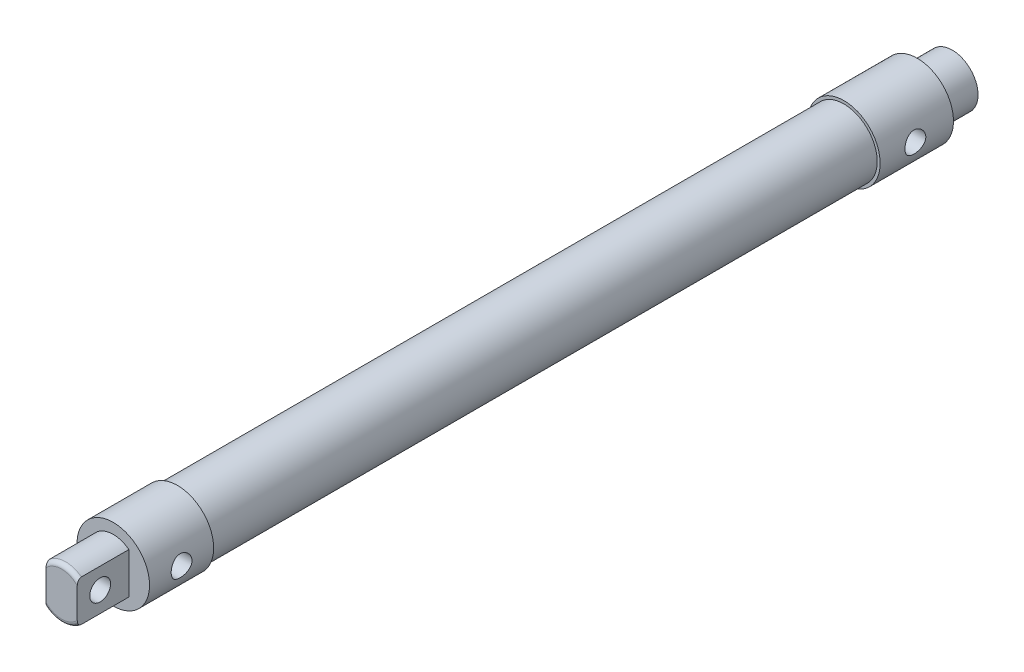
SolidWorks part; units mm, degrees
ref_plane "Front Plane" through (0, 0, 0) normal (0, 0, 1) x (1, 0, 0)
ref_plane "Top Plane" through (0, 0, 0) normal (0, 1, 0) x (1, 0, 0)
ref_plane "Right Plane" through (0, 0, 0) normal (1, 0, 0) x (0, 0, -1)
sketch "Sketch1" plane through (0, 0, 0) normal (0, 0, 1) x (1, 0, 0)
  circle A0 centre (0, 0) radius 10.16
  dimension "D1" = 20.32
extrude "Boss-Extrude1" add sketch "Sketch1" along normal blind 203.2
sketch "Sketch2" plane through (0, 0, 203.2) normal (0, 0, 1) x (1, 0, 0)
  circle A0 centre (0, 0) radius 11.049
  dimension "D1" = 22.098
extrude "Boss-Extrude2" add sketch "Sketch2" along normal blind 19.558 separate body
sketch "Sketch3" plane through (0, 0, 222.758) normal (0, 0, 1) x (1, 0, 0)
  line L0 (0, -7.874) -> (0, 7.874) construction
  line L1 (4.7625, -6.2704) -> (4.7625, 6.2704)
  line L2 (-4.7625, -6.2704) -> (-4.7625, 6.2704)
  line L3 (4.7625, -7.874) -> (4.7625, 7.874) construction
  line L4 (-4.7625, -7.874) -> (-4.7625, 7.874) construction
  arc A0 (4.7625, 6.2704) -> (-4.7625, 6.2704) centre (0, 0) ccw
  arc A1 (-4.7625, -6.2704) -> (4.7625, -6.2704) centre (0, 0) ccw
  dimension "D1" = 15.748
  dimension "D2" = 4.7625
  dimension "D3" = 4.7625
extrude "Boss-Extrude3" add sketch "Sketch3" along normal blind 15.748
sketch "Sketch4" plane through (4.7625, 0, 0) normal (1, 0, 0) x (0, 0, -1)
  line L0 (-238.506, 0) -> (-234.696, 0) construction
  line L1 (-238.506, -6.2704) -> (-238.506, 6.2704) construction
  circle A0 centre (-231.521, 0) radius 3.175
  dimension "D2" = 6.35
  dimension "D1" = 3.81
extrude "Cut-Extrude1" cut sketch "Sketch4" against normal up to next (9.525 mm away)
fillet "Fillet1" radius 1.27 2 edges at (0, 7.874, 238.506) (0, -7.874, 238.506)
sketch "Sketch5" plane through (0, 0, 0) normal (0, 0, -1) x (-1, 0, 0)
  circle A0 centre (0, 0) radius 11.049 construction
  circle A1 centre (0, 0) radius 11.049
extrude "Boss-Extrude4" add sketch "Sketch5" along normal blind 22.352
sketch "Sketch6" plane through (0, 0, -22.352) normal (0, 0, -1) x (-1, 0, 0)
  circle A0 centre (0, 0) radius 7.874
  dimension "D1" = 15.748
extrude "Boss-Extrude5" add sketch "Sketch6" along normal blind 10.668
sketch "Sketch7" plane through (0, 0, -33.02) normal (0, 0, -1) x (-1, 0, 0)
  circle A0 centre (0, 0) radius 3.175
  dimension "D1" = 6.35
extrude "Cut-Extrude2" cut sketch "Sketch7" against normal blind 124.968
ref_plane "Plane1" through (0, 0, 0) normal (1, 0, 0) x (0, 0, -1)
sketch "Sketch8" plane through (0, 0, 0) normal (1, 0, 0) x (0, 0, -1)
  line L0 (-203.2, -11.049) -> (-203.2, 11.049) construction
  line L1 (-203.2, -11.049) -> (-203.2, 11.049) construction
  line L2 (-222.758, 11.049) -> (-222.758, -11.049) construction
  line L3 (-222.758, 11.049) -> (-222.758, -11.049) construction
  line L4 (-212.979, 0) -> (-222.758, 0) construction
  line L5 (-212.979, 0) -> (-203.2, 0) construction
  circle A0 centre (-212.979, 0) radius 3.175
  circle A1 centre (10.7398, 0) radius 3.175
  dimension "D1" = 6.35
  dimension "D2" = 6.35
extrude "Cut-Extrude3" cut sketch "Sketch8" along normal up to next
